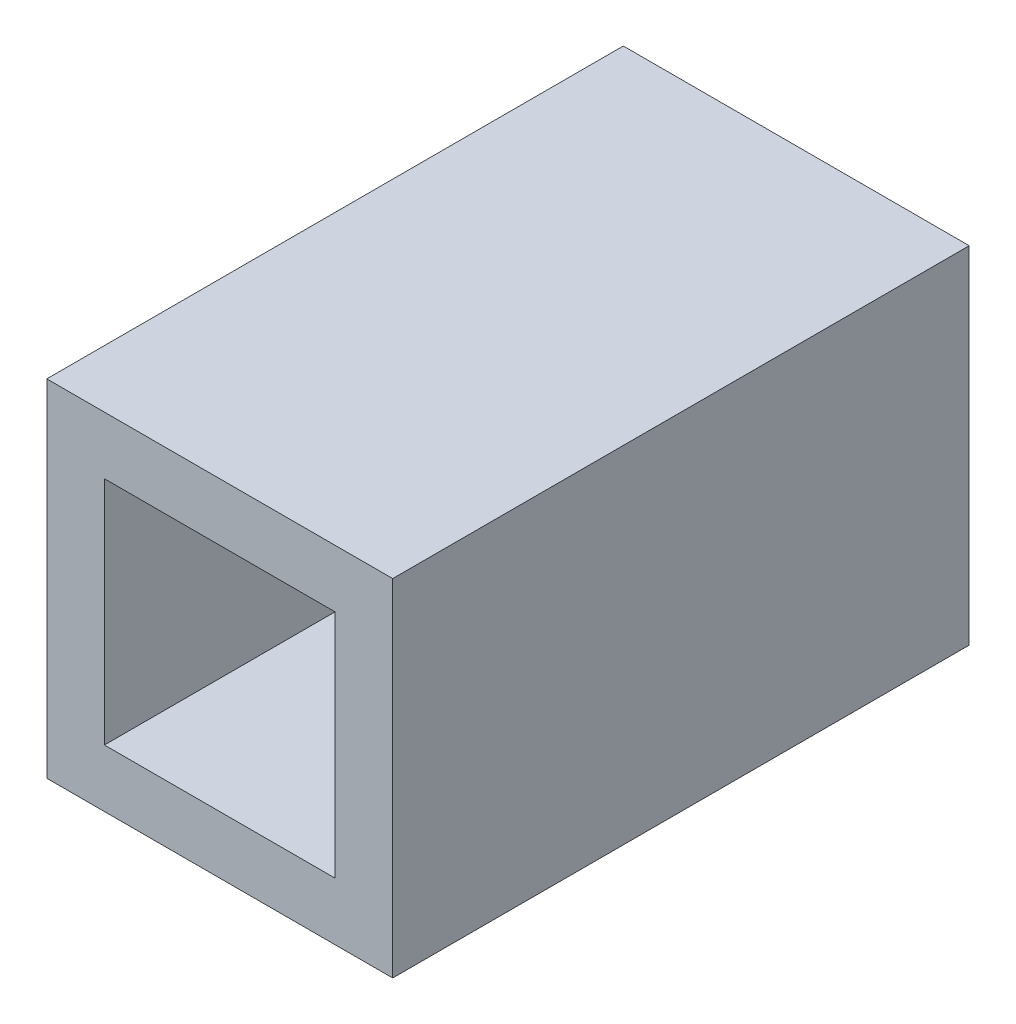
SolidWorks part; units mm, degrees
material "Custom Plastic"
ref_plane "Front Plane" through (0, 0, 0) normal (0, 0, 1) x (1, 0, 0)
ref_plane "Top Plane" through (0, 0, 0) normal (0, 1, 0) x (1, 0, 0)
ref_plane "Right Plane" through (0, 0, 0) normal (1, 0, 0) x (0, 0, -1)
other "Configuration Table"
sketch "Sketch1" plane through (0, 0, 0) normal (1, 0, 0) x (0, 0, -1)
  line L1 (0, 30) -> (-100, 30)
  line L2 (0, 30) -> (0, -30)
  line L3 (0, -30) -> (-100, -30)
  line L4 (-100, 30) -> (-100, -30)
  dimension "D1" = 60
  dimension "D2" = 100
extrude "Boss-Extrude1" add sketch "Sketch1" along normal mid plane 60
sketch "Sketch2" plane through (0, 0, 0) normal (1, 0, 0) x (0, 0, -1)
  line L0 (0, 20) -> (0, -20)
  line L1 (0, -30) -> (0, 30) construction
  line L2 (0, 20) -> (-100, 20)
  line L3 (-100, 30) -> (-100, -30) construction
  line L4 (-100, 20) -> (-100, -20)
  line L5 (-100, -20) -> (0, -20)
  line L9 (0, 0) -> (-100, 0) construction
  line L10 (-100, 30) -> (-100, -30) construction
  point P15 (-50, 0)
  dimension "D1" = 40
extrude "Cut-Extrude1" cut sketch "Sketch2" against normal mid plane 40
